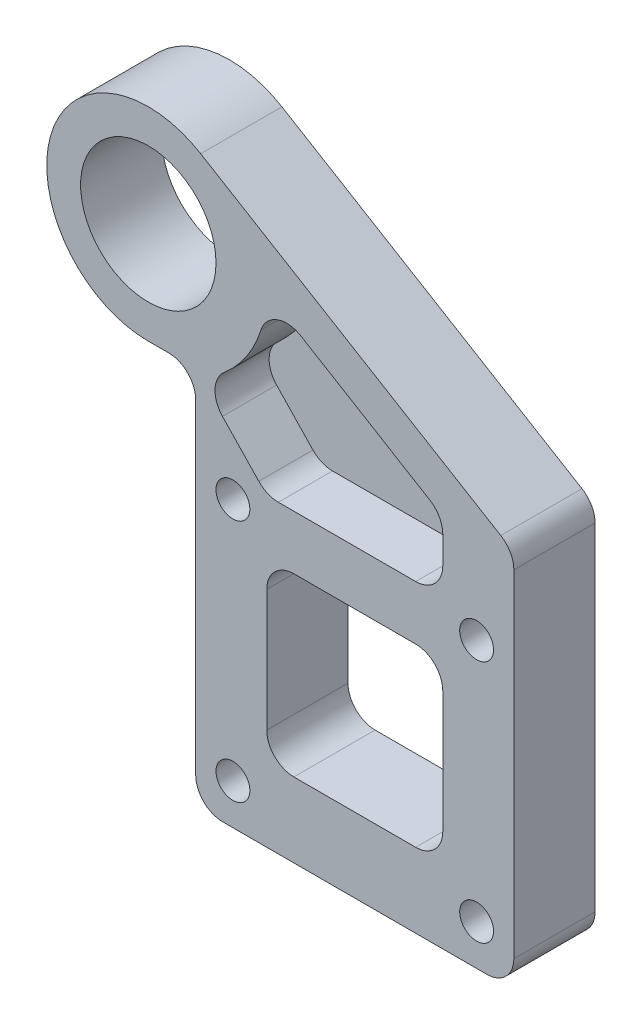
SolidWorks part; units mm, degrees
material "6061-T4 (SS)"
ref_plane "前视基准面" through (0, 0, 0) normal (0, 0, 1) x (1, 0, 0)
ref_plane "上视基准面" through (0, 0, 0) normal (0, 1, 0) x (1, 0, 0)
ref_plane "右视基准面" through (0, 0, 0) normal (1, 0, 0) x (0, 0, -1)
other "Configuration Table"
sketch "草图1" plane through (0, 0, 0) normal (0, 0, 1) x (1, 0, 0)
  line L0 (-11.75, 16) -> (-15.25, 16)
  line L1 (-11.75, -16) -> (11.75, -16)
  line L2 (-11.75, -16) -> (-11.75, 16)
  line L3 (-11.75, 16) -> (11.75, 16)
  line L4 (11.75, -16) -> (11.75, 16)
  line L5 (-11.75, -16) -> (11.75, 16) construction
  line L6 (-11.75, 16) -> (11.75, -16) construction
  line L7 (-11.3818, 29.9255) -> (11.75, 16)
  line L9 (-9, -9) -> (9, -9) construction
  line L10 (-9, -9) -> (-9, 9) construction
  line L11 (-9, 9) -> (9, 9) construction
  line L12 (9, -9) -> (9, 9) construction
  line L13 (-9, -9) -> (9, 9) construction
  line L14 (-9, 9) -> (9, -9) construction
  circle A0 centre (-15.25, 23.5) radius 5
  circle A1 centre (-15.25, 23.5) radius 7.5
  circle A2 centre (9, 9) radius 1.25
  circle A3 centre (-9, 9) radius 1.25
  circle A4 centre (-9, -9) radius 1.25
  circle A5 centre (9, -9) radius 1.25
  point P0 (0, 0)
  point P11 (0, 0)
  dimension "D2" = 10
  dimension "D3" = 15
  dimension "D7" = 2.5
  dimension "D1" = 32
  dimension "D4" = 27
  dimension "D5" = 23.5
  dimension "D6" = 18
extrude "凸台-拉伸1" add sketch "草图1" along normal blind 6 contours A1 L0 L3 L7 | A1 A0 | L1 L4 L3 L2 A5 A4 A3 A2
sketch "草图3" plane through (0, 0, 6) normal (0, 0, 1) x (1, 0, 0)
  line L0 (11.75, -16) -> (11.75, 16) construction
  line L1 (-11.75, -16) -> (11.75, -16)
  line L2 (-11.75, -16) -> (-11.75, -12)
  line L3 (-11.75, -12) -> (11.75, -12)
  line L4 (11.75, -16) -> (11.75, -12)
  line L6 (-6.5, -6.5) -> (6.5, -6.5)
  line L7 (-6.5, -6.5) -> (-6.5, 6.5)
  line L8 (-6.5, 6.5) -> (6.5, 6.5)
  line L9 (6.5, -6.5) -> (6.5, 6.5)
  line L10 (-6.5, -6.5) -> (6.5, 6.5) construction
  line L11 (-6.5, 6.5) -> (6.5, -6.5) construction
  point P7 (0, 0)
  dimension "D1" = 4
  dimension "D2" = 13
extrude "切除-拉伸1" cut sketch "草图3" against normal blind 7
sketch "草图4" plane through (0, 0, 6) normal (0, 0, 1) x (1, 0, 0)
  line L0 (-6.525, 23.5) -> (6.5, 15.6589)
  line L1 (6.5, 15.6589) -> (-11.4235, 15.6589)
  line L2 (-11.4235, 15.6589) -> (-6.5, 10.5)
  line L3 (-6.5, 10.5) -> (6.5, 10.5)
  line L4 (6.5, 10.5) -> (6.5, 15.6589)
  line L5 (-11.3818, 29.9255) -> (11.75, 16) construction
  line L6 (6.5, -6.5) -> (6.5, 6.5) construction
  line L7 (-6.5, 6.5) -> (-6.5, -6.5) construction
  line L8 (6.5, 6.5) -> (-6.5, 6.5) construction
  circle A0 centre (-15.25, 23.5) radius 8.725
  dimension "D1" = 3
  dimension "D2" = 4
extrude "切除-拉伸2" cut sketch "草图4" against normal blind 4 contours A0 L1 L0 | L3 L4 L1 L2
fillet "圆角2" radius 2 13 edges at (-6.5, 10.5, 4) (6.5, 10.5, 4) (6.5, 15.6589, 4) (-6.525, 23.5, 4) (-11.4235, 15.6589, 4) (6.5, 6.5, 3) (-6.5, 6.5, 3) (-6.5, -6.5, 3) (6.5, -6.5, 3) (-11.75, -12, 3) (11.75, 16, 3) (11.75, -12, 3) (-11.75, 16, 3)
